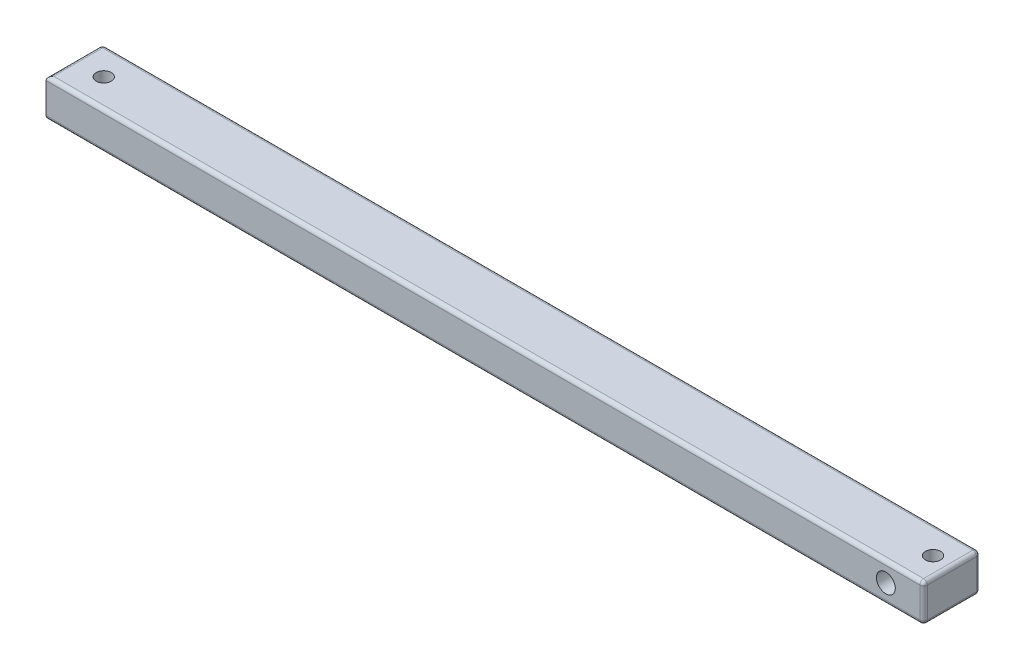
SolidWorks part; units mm, degrees
material "1023 Carbon Steel Sheet (SS)"
ref_plane "Ön Düzlem" through (0, 0, 0) normal (0, 0, 1) x (1, 0, 0)
ref_plane "Üst Düzlem" through (0, 0, 0) normal (0, 1, 0) x (1, 0, 0)
ref_plane "Sağ Düzlem" through (0, 0, 0) normal (1, 0, 0) x (0, 0, -1)
sketch "Sketch1" plane through (0, 0, 0) normal (0, 0, 1) x (1, 0, 0)
  line L0 (-232.5, 0) -> (232.5, 0)
  line L1 (232.5, 0) -> (232.5, 20)
  line L2 (232.5, 20) -> (-232.5, 20)
  line L3 (-232.5, 20) -> (-232.5, 0)
  dimension "D1" = 465
  dimension "D2" = 20
extrude "Boss-Extrude1" add sketch "Sketch1" along normal blind 30
fillet "Fillet1" radius 2 11 edges at (0, 0, 0) (232.5, 10, 0) (0, 20, 0) (-232.5, 10, 0) (-232.5, 20, 15) (-232.5, 0, 15) (232.5, 20, 15) (232.5, 0, 15) (232.5, 10, 30) (0, 0, 30) (0, 20, 30)
sketch "Sketch3" plane through (0, 20, 0) normal (0, 1, 0) x (1, 0, 0)
  line L0 (230.5, -30) -> (-232.5, -30) construction
  line L1 (-232.5, -30) -> (-232.5, -2) construction
  circle A0 centre (-216.9, -15) radius 4
  dimension "D1" = 15
  dimension "D3" = 8
  dimension "D2" = 15.6
extrude "Cut-Extrude2" cut sketch "Sketch3" against normal through all
sketch "Sketch5" plane through (0, 0, 30) normal (0, 0, 1) x (1, 0, 0)
  line L0 (232.5, 18) -> (232.5, 2) construction
  line L1 (-230.5, 20) -> (230.5, 20) construction
  circle A0 centre (212.5, 10) radius 5
  dimension "D1" = 20
  dimension "D3" = 10
  dimension "D2" = 10
extrude "Cut-Extrude4" cut sketch "Sketch5" against normal through all
sketch "Sketch8" plane through (0, 20, 0) normal (0, 1, 0) x (1, 0, 0)
  line L0 (232.5, -2) -> (232.5, -28) construction
  line L1 (-230.5, 0) -> (230.5, 0) construction
  circle A0 centre (222.5, -15) radius 4
  dimension "D1" = 10
  dimension "D3" = 8
  dimension "D2" = 15
extrude "Cut-Extrude5" cut sketch "Sketch8" against normal through all
